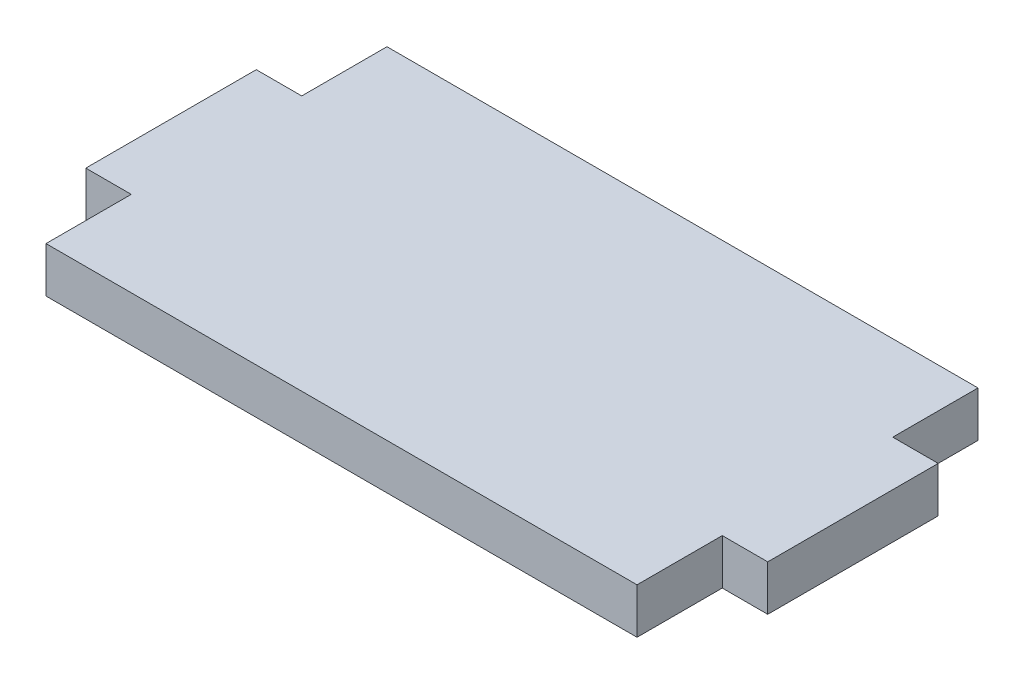
SolidWorks part; units mm, degrees
ref_plane "Ebene vorne" through (0, 0, 0) normal (0, 0, 1) x (1, 0, 0)
ref_plane "Ebene oben" through (0, 0, 0) normal (0, 1, 0) x (1, 0, 0)
ref_plane "Ebene rechts" through (0, 0, 0) normal (1, 0, 0) x (0, 0, -1)
sketch "Skizze1" plane through (0, 0, 0) normal (0, 1, 0) x (1, 0, 0)
  line L0 (-37.3026, 0) -> (31.9356, 0) construction
  line L1 (26, -15) -> (-26, -15)
  line L2 (26, -15) -> (26, -7.5)
  line L3 (26, 15) -> (-26, 15)
  line L4 (-26, -15) -> (-26, -7.5)
  line L5 (26, -15) -> (-26, 15) construction
  line L6 (26, 15) -> (-26, -15) construction
  line L7 (-30, -7.5) -> (-26, -7.5)
  line L8 (-30, -7.5) -> (-30, 7.5)
  line L9 (-30, 7.5) -> (-26, 7.5)
  line L11 (-30, -7.5) -> (-26, 7.5) construction
  line L12 (-30, 7.5) -> (-26, -7.5) construction
  line L13 (-26, 7.5) -> (-26, 15)
  line L14 (26, 7.5) -> (26, 15)
  line L15 (30, -7.5) -> (26, -7.5)
  line L16 (30, -7.5) -> (30, 7.5)
  line L17 (30, 7.5) -> (26, 7.5)
  line L19 (30, -7.5) -> (26, 7.5) construction
  line L20 (30, 7.5) -> (26, -7.5) construction
  point P0 (0, 0)
  point P5 (-28, 0)
  point P13 (28, 0)
  dimension "D1" = 30
  dimension "D2" = 52
  dimension "D3" = 4
  dimension "D4" = 15
  dimension "D5" = 4
extrude "Aufsatz-Linear austragen1" add sketch "Skizze1" along normal blind 4
